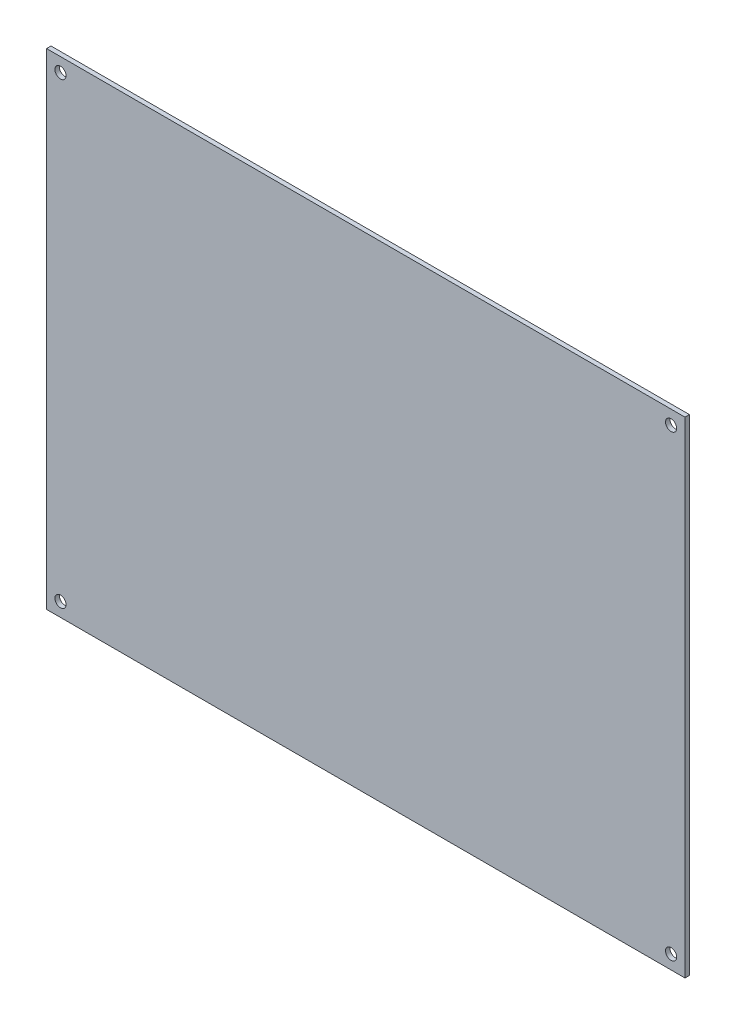
SolidWorks part; units mm, degrees
ref_plane "Front Plane" through (0, 0, 0) normal (0, 0, 1) x (1, 0, 0)
ref_plane "Top Plane" through (0, 0, 0) normal (0, 1, 0) x (1, 0, 0)
ref_plane "Right Plane" through (0, 0, 0) normal (1, 0, 0) x (0, 0, -1)
sketch "Sketch1" plane through (0, 0, 0) normal (0, 0, 1) x (1, 0, 0)
  line L0 (55, 0) -> (-55, 0) construction
  line L1 (-115, -87.5) -> (115, -87.5)
  line L2 (-115, -87.5) -> (-115, 87.5)
  line L3 (-115, 87.5) -> (115, 87.5)
  line L4 (115, -87.5) -> (115, 87.5)
  line L5 (-115, -87.5) -> (115, 87.5) construction
  line L6 (-115, 87.5) -> (115, -87.5) construction
  line L7 (0, -55) -> (0, 55) construction
  circle A0 centre (110, 82.5) radius 2
  circle A1 centre (110, -82.5) radius 2
  circle A2 centre (-110, -82.5) radius 2
  circle A3 centre (-110, 82.5) radius 2
  point P0 (0, 0)
  dimension "D5" = 4
  dimension "D1" = 175
  dimension "D2" = 230
  dimension "D3" = 5
  dimension "D4" = 5
extrude "Boss-Extrude1" add sketch "Sketch1" along normal blind 1.6
